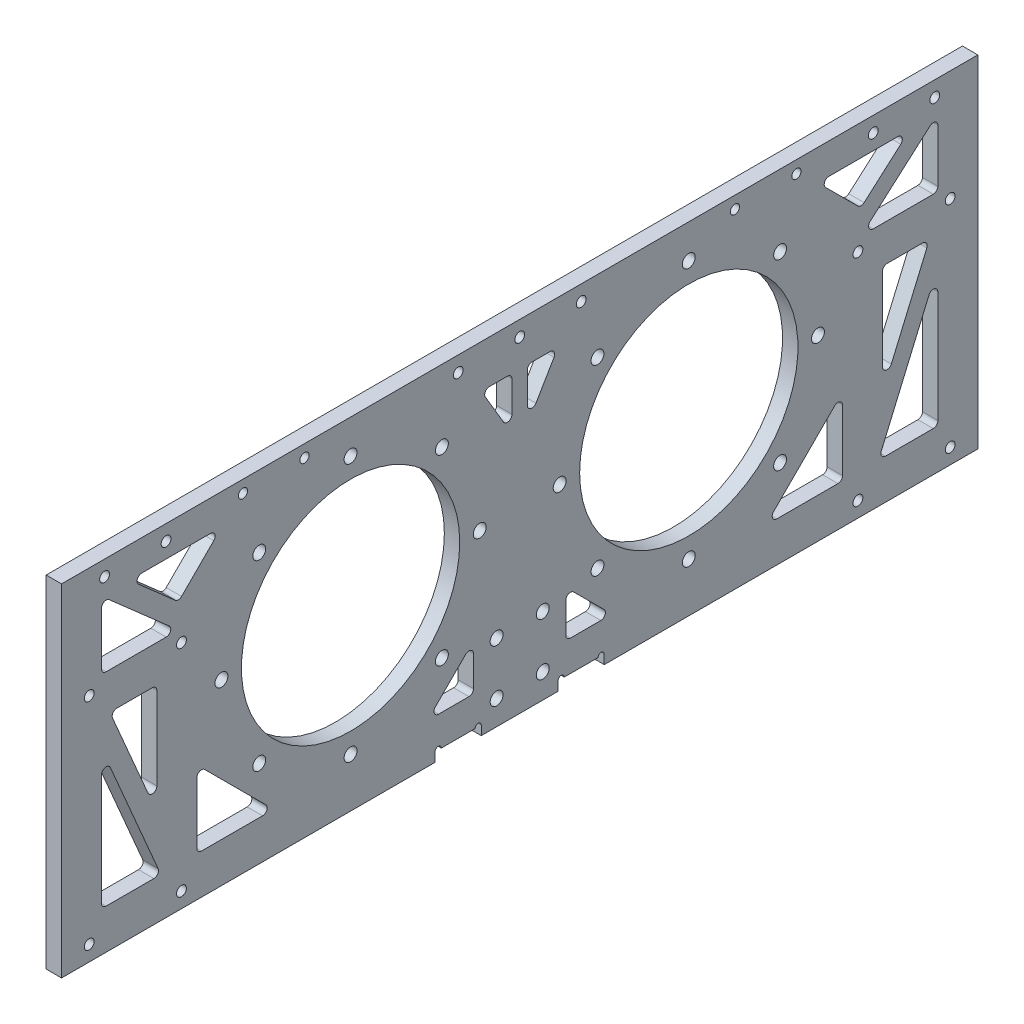
SolidWorks part; units mm, degrees
material "Thornel Mat VMA"
ref_plane "前视基准面" through (0, 0, 0) normal (0, 0, 1) x (1, 0, 0)
ref_plane "上视基准面" through (0, 0, 0) normal (0, 1, 0) x (1, 0, 0)
ref_plane "右视基准面" through (0, 0, 0) normal (1, 0, 0) x (0, 0, -1)
sketch "草图1" plane through (0, 0, 0) normal (1, 0, 0) x (0, 0, -1)
  line L0 (55, 53) -> (55, -58) construction
  line L1 (-94, -58) -> (204, -58)
  line L2 (-94, -58) -> (-94, 53)
  line L3 (-94, 53) -> (204, 53)
  line L4 (204, -58) -> (204, 53)
  line L5 (-35, 49) -> (-15, 49) construction
  line L6 (47.5, -50) -> (62.5, -50) construction
  line L7 (47.5, -50) -> (47.5, -33) construction
  line L8 (47.5, -33) -> (62.5, -33) construction
  line L9 (62.5, -50) -> (62.5, -33) construction
  line L10 (47.5, -50) -> (62.5, -33) construction
  line L11 (47.5, -33) -> (62.5, -50) construction
  line L12 (145, 49) -> (125, 49) construction
  circle A0 centre (0, 0) radius 35.5
  circle A1 centre (0, 0) radius 42 construction
  circle A2 centre (0, 42) radius 2.1
  circle A25 centre (110, 42) radius 2.1
  circle A26 centre (110, 0) radius 42 construction
  circle A27 centre (110, 0) radius 35.5
  circle A28 centre (0, 0) radius 46 construction
  circle A29 centre (110, 0) radius 46 construction
  circle A30 centre (62.5, -33) radius 2.1
  circle A31 centre (47.5, -33) radius 2.1
  circle A32 centre (47.5, -50) radius 2.1
  circle A33 centre (62.5, -50) radius 2.1
  circle A34 centre (-15, 49) radius 1.5
  circle A35 centre (-35, 49) radius 1.5
  circle A36 centre (125, 49) radius 1.5
  circle A37 centre (145, 49) radius 1.5
  circle A38 centre (29.6985, 29.6985) radius 2.1
  circle A39 centre (42, 0) radius 2.1
  circle A40 centre (29.6985, -29.6985) radius 2.1
  circle A41 centre (0, -42) radius 2.1
  circle A42 centre (-29.6985, -29.6985) radius 2.1
  circle A43 centre (-42, 0) radius 2.1
  circle A44 centre (-29.6985, 29.6985) radius 2.1
  circle A45 centre (139.6985, 29.6985) radius 2.1
  circle A46 centre (152, 0) radius 2.1
  circle A47 centre (139.6985, -29.6985) radius 2.1
  circle A48 centre (110, -42) radius 2.1
  circle A49 centre (80.3015, -29.6985) radius 2.1
  circle A50 centre (68, 0) radius 2.1
  circle A51 centre (80.3015, 29.6985) radius 2.1
  point P25 (0, 0)
  point P63 (55, -41.5)
  dimension "D1" = 71
  dimension "D2" = 84
  dimension "D4" = 4.2
  dimension "D9" = 92
  dimension "D13" = 4.2
  dimension "D17" = 3
  dimension "D5" = 58
  dimension "D6" = 53
  dimension "D7" = 94
  dimension "D8" = 110
  dimension "D10" = 25
  dimension "D11" = 17
  dimension "D12" = 15
  dimension "D14" = 70
  dimension "D15" = 20
  dimension "D16" = 4
  dimension "D3" = 8
extrude "凸台-拉伸1" add sketch "草图1" along normal blind 5
sketch "草图2" plane through (5, 0, 0) normal (1, 0, 0) x (0, 0, -1)
  line L0 (-80, 48) -> (-60, 48) construction
  line L1 (55, 53) -> (55, -58) construction
  line L2 (204, 53) -> (-94, 53) construction
  line L3 (-94, -58) -> (204, -58) construction
  line L4 (190, 48) -> (170, 48) construction
  line L5 (-94, 53) -> (-94, -58) construction
  line L6 (35, 48) -> (55, 48) construction
  circle A0 centre (-80, 48) radius 1.6
  circle A1 centre (-60, 48) radius 1.6
  circle A2 centre (170, 48) radius 1.6
  circle A3 centre (190, 48) radius 1.6
  circle A4 centre (35, 48) radius 1.6
  circle A5 centre (55, 48) radius 1.6
  circle A6 centre (75, 48) radius 1.6
  dimension "D1" = 14
  dimension "D4" = 3.2
  dimension "D6" = 3.2
  dimension "D2" = 20
  dimension "D3" = 5
  dimension "D5" = 20
extrude "切除-拉伸1" cut sketch "草图2" against normal through all
sketch "草图3" plane through (5, 0, 0) normal (1, 0, 0) x (0, 0, -1)
  line L0 (-85, -53) -> (-55, -53) construction
  line L1 (-94, 53) -> (-94, -58) construction
  line L2 (-94, -58) -> (204, -58) construction
  line L3 (55, 53) -> (55, -58) construction
  line L4 (204, 53) -> (-94, 53) construction
  line L5 (-85, -53) -> (-85, 17) construction
  line L6 (-85, 17) -> (-55, 17) construction
  line L7 (-55, 17) -> (-55, -53) construction
  line L8 (165, 17) -> (165, -53) construction
  line L9 (195, 17) -> (165, 17) construction
  line L10 (195, -53) -> (195, 17) construction
  line L11 (195, -53) -> (165, -53) construction
  circle A0 centre (-85, -53) radius 1.6
  circle A1 centre (-55, -53) radius 1.6
  circle A2 centre (-85, 17) radius 1.6
  circle A3 centre (-55, 17) radius 1.6
  circle A4 centre (165, 17) radius 1.6
  circle A5 centre (195, 17) radius 1.6
  circle A6 centre (165, -53) radius 1.6
  circle A7 centre (195, -53) radius 1.6
  dimension "D3" = 3.2
  dimension "D1" = 9
  dimension "D2" = 5
  dimension "D4" = 30
  dimension "D5" = 70
extrude "切除-拉伸2" cut sketch "草图3" against normal blind 10
sketch "草图4" plane through (5, 0, 0) normal (1, 0, 0) x (0, 0, -1)
  line L0 (45.1226, 39) -> (51, 39)
  line L1 (52.5, 37.5) -> (52.5, 27.5085)
  line L2 (49.7071, 26.7479) -> (43.8297, 36.7395)
  line L3 (55, 53) -> (55, -58) construction
  line L4 (204, 53) -> (-94, 53) construction
  line L5 (-94, -58) -> (204, -58) construction
  line L6 (57.5, 37.5) -> (57.5, 27.5085)
  line L7 (64.8774, 39) -> (59, 39)
  line L8 (60.2929, 26.7479) -> (66.1703, 36.7395)
  line L9 (-81, -7.257) -> (-81, -43.5)
  line L10 (-85, 17) -> (-55, 17) construction
  line L11 (-85, 17) -> (-85, -53) construction
  line L12 (-85, -53) -> (-55, -53) construction
  line L13 (-55, 17) -> (-55, -53) construction
  line L14 (-79.5, -45) -> (-63.9673, -45)
  line L15 (-62.5886, -42.9091) -> (-78.1213, -6.6661)
  line L16 (-76.0327, 9) -> (-64.5, 9)
  line L17 (-63, 7.5) -> (-63, -19.4097)
  line L18 (-65.8787, -20.0006) -> (-77.4114, 6.9091)
  line L19 (-50, -23.6213) -> (-50, -43.5)
  line L20 (-48.5, -45) -> (-28.6213, -45)
  line L21 (-27.5607, -42.4393) -> (-47.4393, -22.5607)
  line L22 (-81, 39.6819) -> (-81, 22.5)
  line L23 (-79.5, 21) -> (-59.9751, 21)
  line L24 (-58.9842, 23.6261) -> (-78.5091, 40.808)
  line L25 (-67.9426, 43) -> (-45.5391, 43)
  line L26 (-44.4784, 40.4393) -> (-54.9652, 29.9526)
  line L27 (-57.0168, 29.8872) -> (-68.9336, 40.3739)
  line L34 (28.6213, -45) -> (38.5, -45)
  line L35 (40, -43.5) -> (40, -33.6213)
  line L36 (37.4393, -32.5607) -> (27.5607, -42.4393)
  line L37 (72.5607, -32.5607) -> (82.4393, -42.4393)
  line L38 (70, -43.5) -> (70, -33.6213)
  line L39 (81.3787, -45) -> (71.5, -45)
  line L40 (165, 17) -> (165, -53) construction
  line L41 (195, -53) -> (165, -53) construction
  line L42 (195, 17) -> (195, -53) construction
  line L43 (195, 17) -> (165, 17) construction
  line L50 (167.0168, 29.8872) -> (178.9336, 40.3739)
  line L51 (154.4784, 40.4393) -> (164.9652, 29.9526)
  line L52 (177.9426, 43) -> (155.5391, 43)
  line L53 (168.9842, 23.6261) -> (188.5091, 40.808)
  line L54 (189.5, 21) -> (169.9751, 21)
  line L55 (191, 39.6819) -> (191, 22.5)
  line L56 (137.5607, -42.4393) -> (157.4393, -22.5607)
  line L57 (158.5, -45) -> (138.6213, -45)
  line L58 (160, -23.6213) -> (160, -43.5)
  line L59 (175.8787, -20.0006) -> (187.4114, 6.9091)
  line L60 (173, 7.5) -> (173, -19.4097)
  line L61 (186.0327, 9) -> (174.5, 9)
  line L62 (172.5886, -42.9091) -> (188.1213, -6.6661)
  line L63 (189.5, -45) -> (173.9673, -45)
  line L64 (191, -7.257) -> (191, -43.5)
  arc A0 (52.5, 27.5085) -> (49.7071, 26.7479) centre (51, 27.5085) cw
  arc A1 (51, 39) -> (52.5, 37.5) centre (51, 37.5) cw
  arc A2 (45.1226, 39) -> (43.8297, 36.7395) centre (45.1226, 37.5) ccw
  arc A3 (59, 39) -> (57.5, 37.5) centre (59, 37.5) ccw
  arc A4 (57.5, 27.5085) -> (60.2929, 26.7479) centre (59, 27.5085) ccw
  arc A5 (64.8774, 39) -> (66.1703, 36.7395) centre (64.8774, 37.5) cw
  arc A7 (-81, -43.5) -> (-79.5, -45) centre (-79.5, -43.5) ccw
  arc A8 (-63.9673, -45) -> (-62.5886, -42.9091) centre (-63.9673, -43.5) ccw
  arc A9 (-81, -7.257) -> (-78.1213, -6.6661) centre (-79.5, -7.257) cw
  arc A10 (-63, -19.4097) -> (-65.8787, -20.0006) centre (-64.5, -19.4097) cw
  arc A11 (-64.5, 9) -> (-63, 7.5) centre (-64.5, 7.5) cw
  arc A12 (-76.0327, 9) -> (-77.4114, 6.9091) centre (-76.0327, 7.5) ccw
  arc A14 (-28.6213, -45) -> (-27.5607, -42.4393) centre (-28.6213, -43.5) ccw
  arc A15 (-50, -43.5) -> (-48.5, -45) centre (-48.5, -43.5) ccw
  arc A16 (-50, -23.6213) -> (-47.4393, -22.5607) centre (-48.5, -23.6213) cw
  arc A23 (-45.5391, 43) -> (-44.4784, 40.4393) centre (-45.5391, 41.5) cw
  arc A24 (-54.9652, 29.9526) -> (-57.0168, 29.8872) centre (-56.0258, 31.0132) cw
  arc A25 (-67.9426, 43) -> (-68.9336, 40.3739) centre (-67.9426, 41.5) ccw
  arc A26 (-59.9751, 21) -> (-58.9842, 23.6261) centre (-59.9751, 22.5) ccw
  arc A27 (-81, 22.5) -> (-79.5, 21) centre (-79.5, 22.5) ccw
  arc A28 (-81, 39.6819) -> (-78.5091, 40.808) centre (-79.5, 39.6819) cw
  arc A29 (28.6213, -45) -> (27.5607, -42.4393) centre (28.6213, -43.5) cw
  arc A30 (38.5, -45) -> (40, -43.5) centre (38.5, -43.5) ccw
  arc A31 (40, -33.6213) -> (37.4393, -32.5607) centre (38.5, -33.6213) ccw
  arc A32 (70, -33.6213) -> (72.5607, -32.5607) centre (71.5, -33.6213) cw
  arc A33 (71.5, -45) -> (70, -43.5) centre (71.5, -43.5) cw
  arc A34 (81.3787, -45) -> (82.4393, -42.4393) centre (81.3787, -43.5) ccw
  arc A35 (191, 39.6819) -> (188.5091, 40.808) centre (189.5, 39.6819) ccw
  arc A36 (191, 22.5) -> (189.5, 21) centre (189.5, 22.5) cw
  arc A37 (169.9751, 21) -> (168.9842, 23.6261) centre (169.9751, 22.5) cw
  arc A38 (177.9426, 43) -> (178.9336, 40.3739) centre (177.9426, 41.5) cw
  arc A39 (164.9652, 29.9526) -> (167.0168, 29.8872) centre (166.0258, 31.0132) ccw
  arc A40 (155.5391, 43) -> (154.4784, 40.4393) centre (155.5391, 41.5) ccw
  arc A47 (160, -23.6213) -> (157.4393, -22.5607) centre (158.5, -23.6213) ccw
  arc A48 (160, -43.5) -> (158.5, -45) centre (158.5, -43.5) cw
  arc A49 (138.6213, -45) -> (137.5607, -42.4393) centre (138.6213, -43.5) cw
  arc A50 (186.0327, 9) -> (187.4114, 6.9091) centre (186.0327, 7.5) cw
  arc A51 (174.5, 9) -> (173, 7.5) centre (174.5, 7.5) ccw
  arc A52 (173, -19.4097) -> (175.8787, -20.0006) centre (174.5, -19.4097) ccw
  arc A53 (191, -7.257) -> (188.1213, -6.6661) centre (189.5, -7.257) ccw
  arc A54 (173.9673, -45) -> (172.5886, -42.9091) centre (173.9673, -43.5) cw
  arc A55 (191, -43.5) -> (189.5, -45) centre (189.5, -43.5) cw
  point P11 (52.5, 22)
  point P14 (52.5, 39)
  point P17 (42.5, 39)
  point P73 (-25, -45)
  point P76 (-50, -45)
  point P79 (-50, -20)
  point P97 (-41.9177, 43)
  point P102 (-71.9177, 43)
  point P105 (-56, 21)
  point P108 (-81, 21)
  point P111 (-81, 43)
  point P115 (25, -45)
  point P118 (40, -45)
  point P130 (70, -45)
  point P131 (85, -45)
  point P199 (191, 43)
  point P200 (191, 21)
  point P201 (166, 21)
  point P202 (181.9177, 43)
  point P203 (151.9177, 43)
  point P207 (160, -20)
  point P208 (160, -45)
  point P209 (135, -45)
  dimension "D5" = 1.5
  dimension "D13" = 1.5
  dimension "D26" = 1.5
  dimension "D30" = 1.5
  dimension "D23" = 1.5
  dimension "D1" = 2.5
  dimension "D2" = 14
  dimension "D3" = 10
  dimension "D4" = 17
  dimension "D6" = 8
  dimension "D7" = 4
  dimension "D8" = 8
  dimension "D9" = 16
  dimension "D10" = 3
  dimension "D11" = 3
  dimension "D12" = 3
  dimension "D14" = 5
  dimension "D15" = 25
  dimension "D16" = 25
  dimension "D17" = 10
  dimension "D18" = 4
  dimension "D19" = 25
  dimension "D20" = 6
  dimension "D21" = 45
  dimension "D22" = 30
  dimension "D27" = 15
  dimension "D28" = 45
  dimension "D29" = 15
extrude "切除-拉伸3" cut sketch "草图4" against normal through all
sketch "草图6" plane through (5, 0, 0) normal (1, 0, 0) x (0, 0, -1)
  line L0 (42.5, -58) -> (42.5, -55)
  line L1 (-94, -58) -> (204, -58) construction
  line L5 (55, 53) -> (55, -58) construction
  line L6 (204, 53) -> (-94, 53) construction
  line L7 (40.5, -55) -> (29.5, -55)
  line L8 (27.5, -55) -> (27.5, -58)
  line L9 (27.5, -58) -> (42.5, -58)
  line L13 (82.5, -58) -> (67.5, -58)
  line L14 (82.5, -55) -> (82.5, -58)
  line L15 (69.5, -55) -> (80.5, -55)
  line L16 (67.5, -58) -> (67.5, -55)
  arc A0 (27.5, -55) -> (29.5, -55) centre (28.5, -55) cw
  arc A1 (42.5, -55) -> (40.5, -55) centre (41.5, -55) ccw
  arc A2 (67.5, -55) -> (69.5, -55) centre (68.5, -55) cw
  arc A3 (82.5, -55) -> (80.5, -55) centre (81.5, -55) ccw
  dimension "D4" = 1
  dimension "D1" = 25
  dimension "D2" = 3
  dimension "D3" = 15
extrude "切除-拉伸4" cut sketch "草图6" against normal through all
